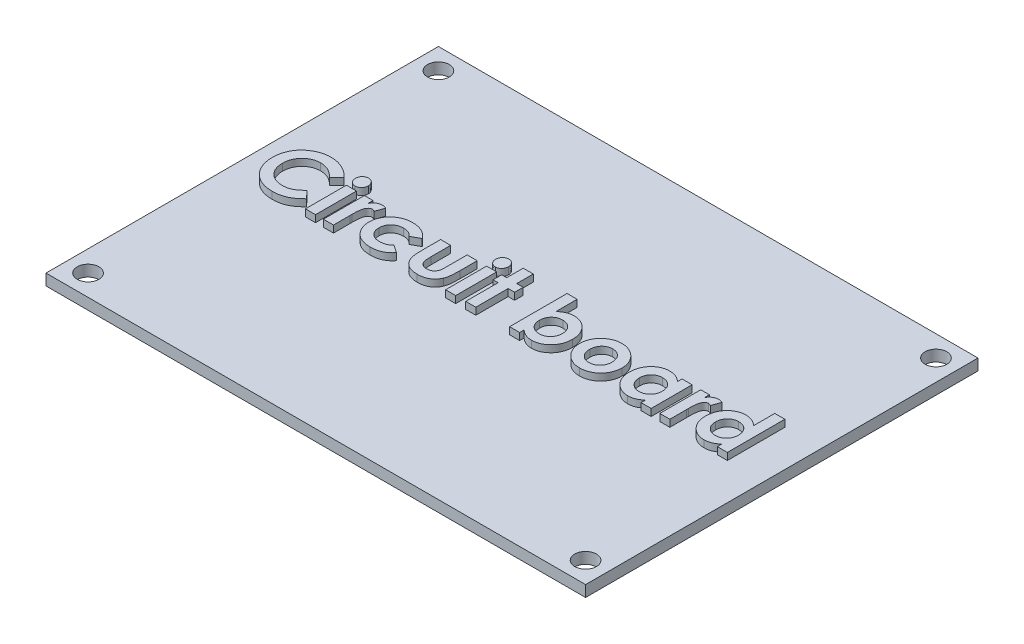
SolidWorks part; units mm, degrees
ref_plane "正面" through (0, 0, 0) normal (0, 0, 1) x (1, 0, 0)
ref_plane "平面" through (0, 0, 0) normal (0, 1, 0) x (1, 0, 0)
ref_plane "右側面" through (0, 0, 0) normal (1, 0, 0) x (0, 0, -1)
sketch "ｽｹｯﾁ1" plane through (0, 0, 0) normal (0, 1, 0) x (1, 0, 0)
  line L0 (-38.5, 28) -> (38.5, 28)
  line L1 (-35.5, 25) -> (35.5, 25) construction
  line L2 (-35.5, 25) -> (-35.5, -25) construction
  line L3 (-35.5, -25) -> (35.5, -25) construction
  line L4 (35.5, 25) -> (35.5, -25) construction
  line L5 (-35.5, 25) -> (35.5, -25) construction
  line L6 (-35.5, -25) -> (35.5, 25) construction
  line L7 (38.5, 28) -> (38.5, -28)
  line L8 (-38.5, -28) -> (38.5, -28)
  line L9 (-38.5, 28) -> (-38.5, -28)
  circle A0 centre (-35.5, 25) radius 1.55
  circle A1 centre (35.5, 25) radius 1.55
  circle A2 centre (35.5, -25) radius 1.55
  circle A3 centre (-35.5, -25) radius 1.55
  point P0 (0, 0)
  dimension "D3" = 3.1
  dimension "D1" = 71
  dimension "D2" = 50
  dimension "D4" = 3
extrude "ﾎﾞｽ - 押し出し1" add sketch "ｽｹｯﾁ1" along normal blind 1.6
sketch "ｽｹｯﾁ2" plane through (0, 1.6, 0) normal (0, 1, 0) x (1, 0, 0)
  text T0 "<b>Circuit board</b>" font "Century Gothic" height 8
extrude "ﾎﾞｽ - 押し出し2" add sketch "ｽｹｯﾁ2" along normal blind 1
